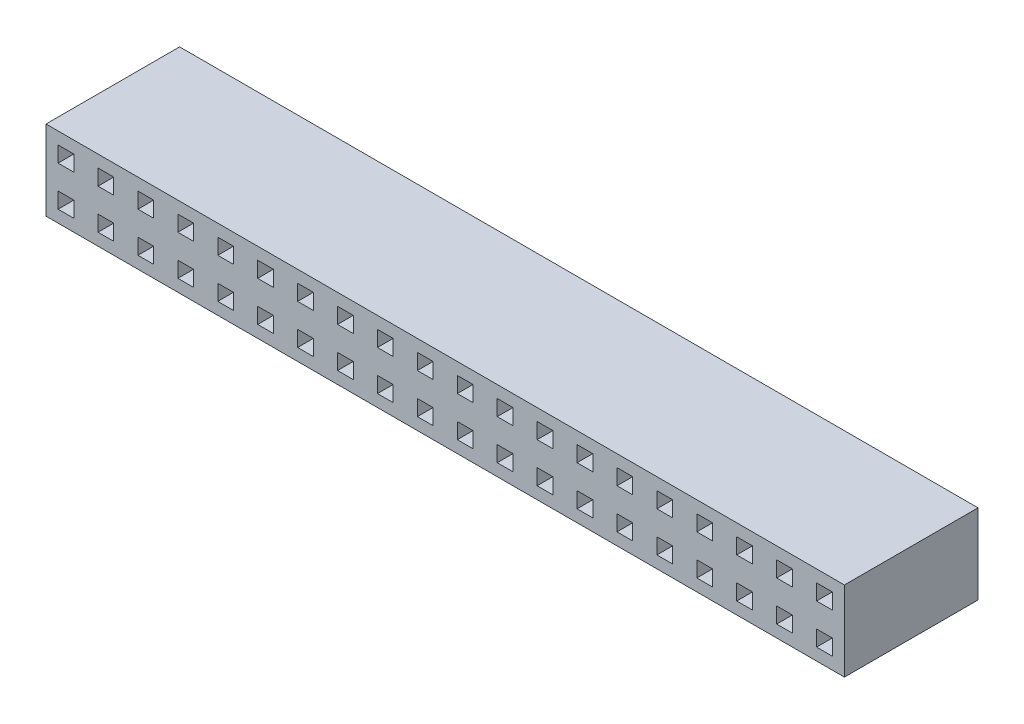
SolidWorks part; units mm, degrees
ref_plane "Front Plane" through (0, 0, 0) normal (0, 0, 1) x (1, 0, 0)
ref_plane "Top Plane" through (0, 0, 0) normal (0, 1, 0) x (1, 0, 0)
ref_plane "Right Plane" through (0, 0, 0) normal (1, 0, 0) x (0, 0, -1)
ref_plane "Plane_z4_1" through (0, 0, 4.1) normal (0, 0, 1) x (1, 0, 0)
sketch "Sketch1" plane through (0, 0, 4.1) normal (0, 0, 1) x (1, 0, 0)
  line L1 (7.1, 49.96) -> (57.9, 49.96)
  line L2 (7.1, 49.96) -> (7.1, 55.04)
  line L3 (7.1, 55.04) -> (57.9, 55.04)
  line L4 (57.9, 49.96) -> (57.9, 55.04)
extrude "Socket_Body" add sketch "Sketch1" along normal blind 8.5
sketch "Sketch2" plane through (0, 0, 0) normal (0, 0, 1) x (1, 0, 0)
  line L1 (7.87, 50.73) -> (8.87, 50.73)
  line L2 (7.87, 50.73) -> (7.87, 51.73)
  line L3 (7.87, 51.73) -> (8.87, 51.73)
  line L4 (8.87, 50.73) -> (8.87, 51.73)
  line L6 (7.87, 53.27) -> (8.87, 53.27)
  line L7 (7.87, 53.27) -> (7.87, 54.27)
  line L8 (7.87, 54.27) -> (8.87, 54.27)
  line L9 (8.87, 53.27) -> (8.87, 54.27)
  line L11 (10.41, 50.73) -> (11.41, 50.73)
  line L12 (10.41, 50.73) -> (10.41, 51.73)
  line L13 (10.41, 51.73) -> (11.41, 51.73)
  line L14 (11.41, 50.73) -> (11.41, 51.73)
  line L16 (10.41, 53.27) -> (11.41, 53.27)
  line L17 (10.41, 53.27) -> (10.41, 54.27)
  line L18 (10.41, 54.27) -> (11.41, 54.27)
  line L19 (11.41, 53.27) -> (11.41, 54.27)
  line L21 (12.95, 50.73) -> (13.95, 50.73)
  line L22 (12.95, 50.73) -> (12.95, 51.73)
  line L23 (12.95, 51.73) -> (13.95, 51.73)
  line L24 (13.95, 50.73) -> (13.95, 51.73)
  line L26 (12.95, 53.27) -> (13.95, 53.27)
  line L27 (12.95, 53.27) -> (12.95, 54.27)
  line L28 (12.95, 54.27) -> (13.95, 54.27)
  line L29 (13.95, 53.27) -> (13.95, 54.27)
  line L31 (15.49, 50.73) -> (16.49, 50.73)
  line L32 (15.49, 50.73) -> (15.49, 51.73)
  line L33 (15.49, 51.73) -> (16.49, 51.73)
  line L34 (16.49, 50.73) -> (16.49, 51.73)
  line L36 (15.49, 53.27) -> (16.49, 53.27)
  line L37 (15.49, 53.27) -> (15.49, 54.27)
  line L38 (15.49, 54.27) -> (16.49, 54.27)
  line L39 (16.49, 53.27) -> (16.49, 54.27)
  line L41 (18.03, 50.73) -> (19.03, 50.73)
  line L42 (18.03, 50.73) -> (18.03, 51.73)
  line L43 (18.03, 51.73) -> (19.03, 51.73)
  line L44 (19.03, 50.73) -> (19.03, 51.73)
  line L46 (18.03, 53.27) -> (19.03, 53.27)
  line L47 (18.03, 53.27) -> (18.03, 54.27)
  line L48 (18.03, 54.27) -> (19.03, 54.27)
  line L49 (19.03, 53.27) -> (19.03, 54.27)
  line L51 (20.57, 50.73) -> (21.57, 50.73)
  line L52 (20.57, 50.73) -> (20.57, 51.73)
  line L53 (20.57, 51.73) -> (21.57, 51.73)
  line L54 (21.57, 50.73) -> (21.57, 51.73)
  line L56 (20.57, 53.27) -> (21.57, 53.27)
  line L57 (20.57, 53.27) -> (20.57, 54.27)
  line L58 (20.57, 54.27) -> (21.57, 54.27)
  line L59 (21.57, 53.27) -> (21.57, 54.27)
  line L61 (23.11, 50.73) -> (24.11, 50.73)
  line L62 (23.11, 50.73) -> (23.11, 51.73)
  line L63 (23.11, 51.73) -> (24.11, 51.73)
  line L64 (24.11, 50.73) -> (24.11, 51.73)
  line L66 (23.11, 53.27) -> (24.11, 53.27)
  line L67 (23.11, 53.27) -> (23.11, 54.27)
  line L68 (23.11, 54.27) -> (24.11, 54.27)
  line L69 (24.11, 53.27) -> (24.11, 54.27)
  line L71 (25.65, 50.73) -> (26.65, 50.73)
  line L72 (25.65, 50.73) -> (25.65, 51.73)
  line L73 (25.65, 51.73) -> (26.65, 51.73)
  line L74 (26.65, 50.73) -> (26.65, 51.73)
  line L76 (25.65, 53.27) -> (26.65, 53.27)
  line L77 (25.65, 53.27) -> (25.65, 54.27)
  line L78 (25.65, 54.27) -> (26.65, 54.27)
  line L79 (26.65, 53.27) -> (26.65, 54.27)
  line L81 (28.19, 50.73) -> (29.19, 50.73)
  line L82 (28.19, 50.73) -> (28.19, 51.73)
  line L83 (28.19, 51.73) -> (29.19, 51.73)
  line L84 (29.19, 50.73) -> (29.19, 51.73)
  line L86 (28.19, 53.27) -> (29.19, 53.27)
  line L87 (28.19, 53.27) -> (28.19, 54.27)
  line L88 (28.19, 54.27) -> (29.19, 54.27)
  line L89 (29.19, 53.27) -> (29.19, 54.27)
  line L91 (30.73, 50.73) -> (31.73, 50.73)
  line L92 (30.73, 50.73) -> (30.73, 51.73)
  line L93 (30.73, 51.73) -> (31.73, 51.73)
  line L94 (31.73, 50.73) -> (31.73, 51.73)
  line L96 (30.73, 53.27) -> (31.73, 53.27)
  line L97 (30.73, 53.27) -> (30.73, 54.27)
  line L98 (30.73, 54.27) -> (31.73, 54.27)
  line L99 (31.73, 53.27) -> (31.73, 54.27)
  line L101 (33.27, 50.73) -> (34.27, 50.73)
  line L102 (33.27, 50.73) -> (33.27, 51.73)
  line L103 (33.27, 51.73) -> (34.27, 51.73)
  line L104 (34.27, 50.73) -> (34.27, 51.73)
  line L106 (33.27, 53.27) -> (34.27, 53.27)
  line L107 (33.27, 53.27) -> (33.27, 54.27)
  line L108 (33.27, 54.27) -> (34.27, 54.27)
  line L109 (34.27, 53.27) -> (34.27, 54.27)
  line L111 (35.81, 50.73) -> (36.81, 50.73)
  line L112 (35.81, 50.73) -> (35.81, 51.73)
  line L113 (35.81, 51.73) -> (36.81, 51.73)
  line L114 (36.81, 50.73) -> (36.81, 51.73)
  line L116 (35.81, 53.27) -> (36.81, 53.27)
  line L117 (35.81, 53.27) -> (35.81, 54.27)
  line L118 (35.81, 54.27) -> (36.81, 54.27)
  line L119 (36.81, 53.27) -> (36.81, 54.27)
  line L121 (38.35, 50.73) -> (39.35, 50.73)
  line L122 (38.35, 50.73) -> (38.35, 51.73)
  line L123 (38.35, 51.73) -> (39.35, 51.73)
  line L124 (39.35, 50.73) -> (39.35, 51.73)
  line L126 (38.35, 53.27) -> (39.35, 53.27)
  line L127 (38.35, 53.27) -> (38.35, 54.27)
  line L128 (38.35, 54.27) -> (39.35, 54.27)
  line L129 (39.35, 53.27) -> (39.35, 54.27)
  line L131 (40.89, 50.73) -> (41.89, 50.73)
  line L132 (40.89, 50.73) -> (40.89, 51.73)
  line L133 (40.89, 51.73) -> (41.89, 51.73)
  line L134 (41.89, 50.73) -> (41.89, 51.73)
  line L136 (40.89, 53.27) -> (41.89, 53.27)
  line L137 (40.89, 53.27) -> (40.89, 54.27)
  line L138 (40.89, 54.27) -> (41.89, 54.27)
  line L139 (41.89, 53.27) -> (41.89, 54.27)
  line L141 (43.43, 50.73) -> (44.43, 50.73)
  line L142 (43.43, 50.73) -> (43.43, 51.73)
  line L143 (43.43, 51.73) -> (44.43, 51.73)
  line L144 (44.43, 50.73) -> (44.43, 51.73)
  line L146 (43.43, 53.27) -> (44.43, 53.27)
  line L147 (43.43, 53.27) -> (43.43, 54.27)
  line L148 (43.43, 54.27) -> (44.43, 54.27)
  line L149 (44.43, 53.27) -> (44.43, 54.27)
  line L151 (45.97, 50.73) -> (46.97, 50.73)
  line L152 (45.97, 50.73) -> (45.97, 51.73)
  line L153 (45.97, 51.73) -> (46.97, 51.73)
  line L154 (46.97, 50.73) -> (46.97, 51.73)
  line L156 (45.97, 53.27) -> (46.97, 53.27)
  line L157 (45.97, 53.27) -> (45.97, 54.27)
  line L158 (45.97, 54.27) -> (46.97, 54.27)
  line L159 (46.97, 53.27) -> (46.97, 54.27)
  line L161 (48.51, 50.73) -> (49.51, 50.73)
  line L162 (48.51, 50.73) -> (48.51, 51.73)
  line L163 (48.51, 51.73) -> (49.51, 51.73)
  line L164 (49.51, 50.73) -> (49.51, 51.73)
  line L166 (48.51, 53.27) -> (49.51, 53.27)
  line L167 (48.51, 53.27) -> (48.51, 54.27)
  line L168 (48.51, 54.27) -> (49.51, 54.27)
  line L169 (49.51, 53.27) -> (49.51, 54.27)
  line L171 (51.05, 50.73) -> (52.05, 50.73)
  line L172 (51.05, 50.73) -> (51.05, 51.73)
  line L173 (51.05, 51.73) -> (52.05, 51.73)
  line L174 (52.05, 50.73) -> (52.05, 51.73)
  line L176 (51.05, 53.27) -> (52.05, 53.27)
  line L177 (51.05, 53.27) -> (51.05, 54.27)
  line L178 (51.05, 54.27) -> (52.05, 54.27)
  line L179 (52.05, 53.27) -> (52.05, 54.27)
  line L181 (53.59, 50.73) -> (54.59, 50.73)
  line L182 (53.59, 50.73) -> (53.59, 51.73)
  line L183 (53.59, 51.73) -> (54.59, 51.73)
  line L184 (54.59, 50.73) -> (54.59, 51.73)
  line L186 (53.59, 53.27) -> (54.59, 53.27)
  line L187 (53.59, 53.27) -> (53.59, 54.27)
  line L188 (53.59, 54.27) -> (54.59, 54.27)
  line L189 (54.59, 53.27) -> (54.59, 54.27)
  line L191 (56.13, 50.73) -> (57.13, 50.73)
  line L192 (56.13, 50.73) -> (56.13, 51.73)
  line L193 (56.13, 51.73) -> (57.13, 51.73)
  line L194 (57.13, 50.73) -> (57.13, 51.73)
  line L196 (56.13, 53.27) -> (57.13, 53.27)
  line L197 (56.13, 53.27) -> (56.13, 54.27)
  line L198 (56.13, 54.27) -> (57.13, 54.27)
  line L199 (57.13, 53.27) -> (57.13, 54.27)
extrude "Socket_Holes" cut sketch "Sketch2" against normal through all and the other way through all
